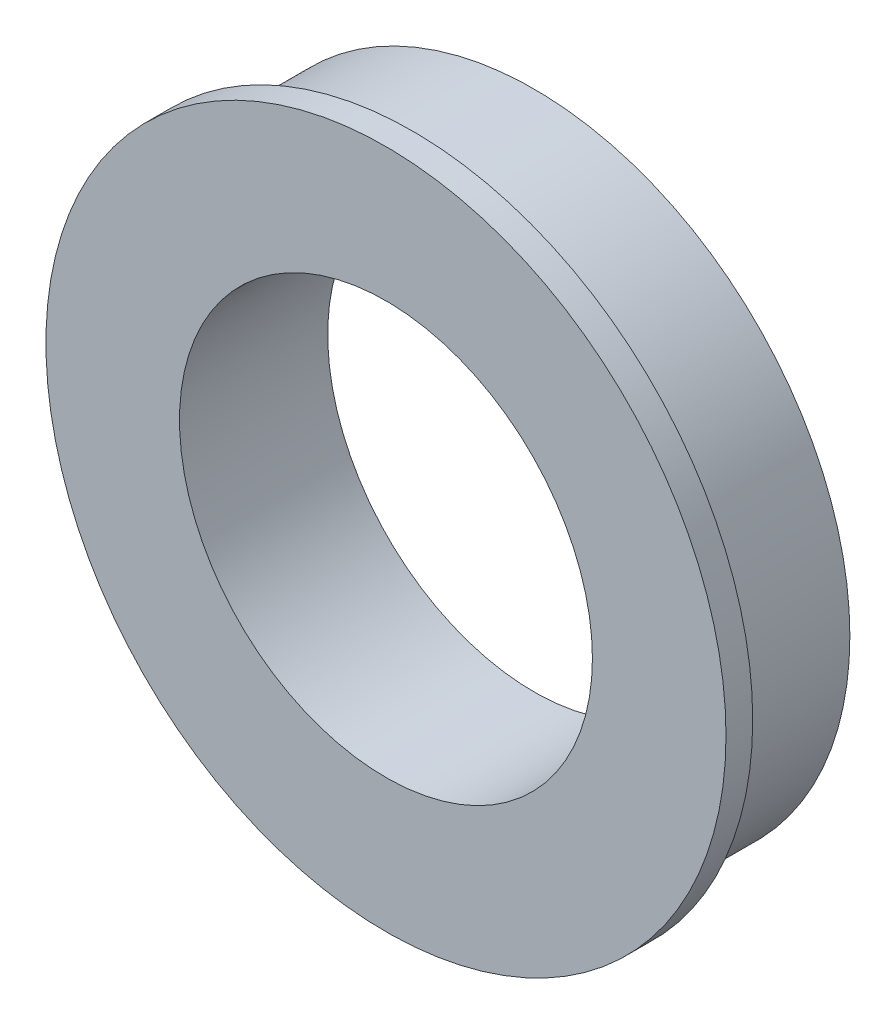
SolidWorks part; units mm, degrees
ref_plane "前视基准面" through (0, 0, 0) normal (0, 0, 1) x (1, 0, 0)
ref_plane "上视基准面" through (0, 0, 0) normal (0, 1, 0) x (1, 0, 0)
ref_plane "右视基准面" through (0, 0, 0) normal (1, 0, 0) x (0, 0, -1)
sketch "草图1" plane through (0, 0, 0) normal (0, 0, 1) x (1, 0, 0)
  circle A0 centre (0, 0) radius 13
  circle A1 centre (0, 0) radius 8.5
  dimension "D1" = 17
  dimension "D2" = 26
extrude "凸台-拉伸1" add sketch "草图1" along normal blind 5
sketch "草图2" plane through (0, 0, 5) normal (0, 0, 1) x (1, 0, 0)
  circle A0 centre (0, 0) radius 8.5
  circle A1 centre (0, 0) radius 14
  dimension "D1" = 28
extrude "凸台-拉伸2" add sketch "草图2" along normal blind 1.1
